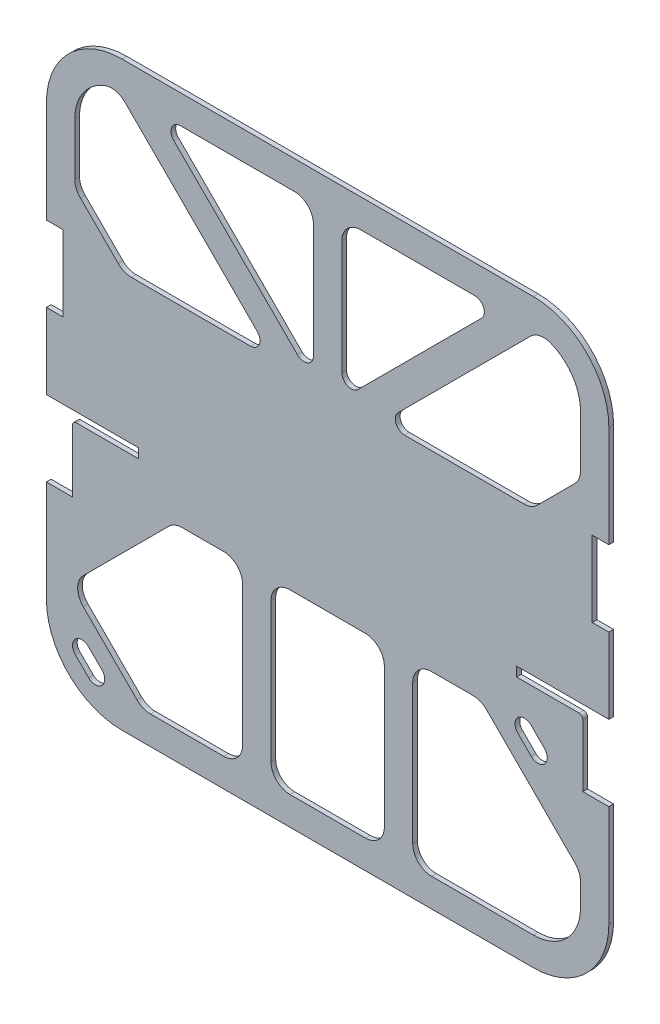
SolidWorks part; units mm, degrees
material "Thornel Mat VMA"
ref_plane "Front Plane" through (0, 0, 0) normal (0, 0, 1) x (1, 0, 0)
ref_plane "Top Plane" through (0, 0, 0) normal (0, 1, 0) x (1, 0, 0)
ref_plane "Right Plane" through (0, 0, 0) normal (1, 0, 0) x (0, 0, -1)
ref_plane "Plane1" through (0, 0, -447.675) normal (0, 0, 1) x (1, 0, 0)
sketch "Sketch1" plane through (0, 0, -447.675) normal (0, 0, 1) x (1, 0, 0)
  line L0 (-25.4, -85.725) -> (25.4, -85.725) construction
  line L1 (25.4, -111.125) -> (-25.4, -111.125) construction
  line L2 (94.488, -85.725) -> (88.9, -85.725)
  line L3 (88.9, -85.725) -> (88.9, -60.325)
  line L4 (88.9, -60.325) -> (-88.9, -60.325) construction
  line L5 (-88.9, -60.325) -> (-88.9, -85.725)
  line L6 (-88.9, -85.725) -> (-94.488, -85.725)
  line L7 (-94.488, -85.725) -> (-94.488, -111.125)
  line L8 (-94.488, -111.125) -> (-63.5, -111.125)
  line L9 (-63.5, -111.125) -> (-63.5, -114.3)
  line L10 (-63.5, -114.3) -> (-84.455, -114.3)
  line L11 (-85.725, -115.57) -> (-85.725, -136.525)
  line L12 (-85.725, -136.525) -> (85.725, -136.525) construction
  line L13 (85.725, -136.525) -> (85.725, -115.57)
  line L14 (84.455, -114.3) -> (63.5, -114.3)
  line L15 (63.5, -114.3) -> (63.5, -111.125)
  line L16 (63.5, -111.125) -> (94.488, -111.125)
  line L17 (94.488, -111.125) -> (94.488, -85.725)
  line L18 (-85.725, -136.525) -> (-94.488, -136.525)
  line L19 (-94.488, -136.525) -> (-94.488, -170.688)
  line L20 (85.725, -136.525) -> (94.488, -136.525)
  line L21 (94.488, -136.525) -> (94.488, -170.688)
  line L22 (69.088, -196.088) -> (-69.088, -196.088)
  line L23 (-88.9, -60.325) -> (-94.488, -60.325)
  line L24 (-94.488, -60.325) -> (-94.488, -26.162)
  line L25 (-69.088, -0.762) -> (69.088, -0.762)
  line L26 (94.488, -26.162) -> (94.488, -60.325)
  line L27 (94.488, -60.325) -> (88.9, -60.325)
  line L28 (0, 0) -> (0, 50000) construction
  line L29 (-84.963, -170.688) -> (-84.963, -163.089) construction
  line L30 (-83.1031, -158.5988) -> (-53.3642, -128.8599) construction
  line L31 (-48.874, -127) -> (-34.925, -127)
  line L32 (-28.575, -133.35) -> (-28.575, -180.213)
  line L33 (-34.925, -186.563) -> (-69.088, -186.563) construction
  line L34 (28.575, -133.35) -> (28.575, -180.213)
  line L35 (-12.7, -127) -> (12.7, -127)
  line L36 (-19.05, -133.35) -> (-19.05, -180.213)
  line L37 (-12.7, -186.563) -> (12.7, -186.563)
  line L38 (19.05, -133.35) -> (19.05, -180.213)
  line L39 (34.925, -186.563) -> (69.088, -186.563)
  line L40 (84.963, -170.688) -> (84.963, -163.089)
  line L41 (83.1031, -158.5988) -> (53.3642, -128.8599)
  line L42 (48.874, -127) -> (34.925, -127)
  line L43 (-84.963, -26.162) -> (-84.963, -43.6712)
  line L44 (-83.1031, -48.1614) -> (-70.4016, -60.8629)
  line L45 (-68.1297, -12.8259) -> (-23.6529, -57.3027)
  line L46 (-25.898, -62.7227) -> (-65.9115, -62.7227)
  line L47 (-49.4612, -10.3589) -> (-11.1125, -10.3589)
  line L48 (-4.7625, -16.7089) -> (-4.7625, -55.0576)
  line L49 (-10.1826, -57.3027) -> (-51.7063, -15.7789)
  line L50 (4.7625, -16.7089) -> (4.7625, -55.0576)
  line L51 (10.1826, -57.3027) -> (51.7063, -15.7789)
  line L52 (49.4612, -10.3589) -> (11.1125, -10.3589)
  line L53 (68.1297, -12.8259) -> (23.6529, -57.3027)
  line L54 (25.898, -62.7227) -> (65.9115, -62.7227)
  line L55 (70.4016, -60.8629) -> (83.1031, -48.1614)
  line L56 (84.963, -43.6712) -> (84.963, -26.162)
  line L57 (-67.5792, -10.3589) -> (-15.2154, -62.7227) construction
  line L58 (66.1388, -128.1641) -> (70.629, -132.6543) construction
  line L59 (68.3839, -125.9191) -> (72.874, -130.4092)
  line L60 (63.8938, -130.4092) -> (68.3839, -134.8993)
  line L61 (-82.5584, -179.6683) -> (-78.0683, -184.1584) construction
  line L62 (-80.3133, -177.4232) -> (-75.8232, -181.9133)
  line L63 (-84.8034, -181.9133) -> (-80.3133, -186.4034)
  line L64 (-82.1401, -166.6161) -> (-64.0531, -184.7031)
  line L65 (-59.563, -186.563) -> (-34.925, -186.563)
  line L66 (-53.3642, -128.8599) -> (-82.1401, -157.6359)
  arc A0 (25.4, -85.725) -> (25.4, -111.125) centre (25.4, -98.425) cw construction
  arc A1 (-25.4, -111.125) -> (-25.4, -85.725) centre (-25.4, -98.425) cw construction
  circle A2 centre (-83.82, -84.8367) radius 1.5875 construction
  arc A3 (94.488, -170.688) -> (69.088, -196.088) centre (69.088, -170.688) cw
  arc A4 (-94.488, -170.688) -> (-69.088, -196.088) centre (-69.088, -170.688) ccw
  arc A5 (69.088, -0.762) -> (94.488, -26.162) centre (69.088, -26.162) cw
  arc A6 (-94.488, -26.162) -> (-69.088, -0.762) centre (-69.088, -26.162) cw
  arc A7 (-84.963, -26.162) -> (-74.9744, -11.4187) centre (-69.088, -26.162) cw
  arc A8 (74.9744, -11.4187) -> (84.963, -26.162) centre (69.088, -26.162) cw
  arc A9 (84.963, -170.688) -> (69.088, -186.563) centre (69.088, -170.688) cw
  arc A10 (-84.963, -170.688) -> (-69.088, -186.563) centre (-69.088, -170.688) ccw construction
  circle A11 centre (-63.5, -114.3) radius 17.4625 construction
  circle A12 centre (-85.725, -136.525) radius 17.4625 construction
  arc A13 (28.575, -133.35) -> (34.925, -127) centre (34.925, -133.35) cw
  arc A14 (53.3642, -128.8599) -> (48.874, -127) centre (48.874, -133.35) ccw
  arc A15 (84.963, -163.089) -> (83.1031, -158.5988) centre (78.613, -163.089) ccw
  arc A16 (28.575, -180.213) -> (34.925, -186.563) centre (34.925, -180.213) ccw
  arc A17 (-19.05, -180.213) -> (-12.7, -186.563) centre (-12.7, -180.213) ccw
  arc A18 (12.7, -186.563) -> (19.05, -180.213) centre (12.7, -180.213) ccw
  arc A19 (12.7, -127) -> (19.05, -133.35) centre (12.7, -133.35) cw
  arc A20 (-12.7, -127) -> (-19.05, -133.35) centre (-12.7, -133.35) ccw
  arc A21 (-28.575, -180.213) -> (-34.925, -186.563) centre (-34.925, -180.213) cw
  arc A22 (-34.925, -127) -> (-28.575, -133.35) centre (-34.925, -133.35) cw
  arc A23 (-53.3642, -128.8599) -> (-48.874, -127) centre (-48.874, -133.35) cw
  arc A24 (-84.963, -163.089) -> (-83.1031, -158.5988) centre (-78.613, -163.089) cw construction
  circle A25 centre (-88.9, -60.325) radius 12.7 construction
  arc A26 (65.9115, -62.7227) -> (70.4016, -60.8629) centre (65.9115, -56.3727) ccw
  arc A27 (83.1031, -48.1614) -> (84.963, -43.6712) centre (78.613, -43.6712) ccw
  arc A28 (69.088, -10.287) -> (84.963, -26.162) centre (69.088, -26.162) cw construction
  arc A29 (68.1297, -12.8259) -> (74.9744, -11.4187) centre (72.6199, -17.316) cw
  arc A30 (4.7625, -16.7089) -> (11.1125, -10.3589) centre (11.1125, -16.7089) cw
  arc A31 (-11.1125, -10.3589) -> (-4.7625, -16.7089) centre (-11.1125, -16.7089) cw
  arc A32 (-84.963, -26.162) -> (-69.088, -10.287) centre (-69.088, -26.162) cw construction
  arc A33 (-68.1297, -12.8259) -> (-74.9744, -11.4187) centre (-72.6199, -17.316) ccw
  arc A34 (-70.4016, -60.8629) -> (-65.9115, -62.7227) centre (-65.9115, -56.3727) ccw
  arc A35 (-84.963, -43.6712) -> (-83.1031, -48.1614) centre (-78.613, -43.6712) ccw
  arc A36 (23.6529, -57.3027) -> (25.898, -62.7227) centre (25.898, -59.5477) ccw
  arc A37 (51.7063, -15.7789) -> (49.4612, -10.3589) centre (49.4612, -13.5339) ccw
  arc A38 (4.7625, -55.0576) -> (10.1826, -57.3027) centre (7.9375, -55.0576) ccw
  arc A39 (-23.6529, -57.3027) -> (-25.898, -62.7227) centre (-25.898, -59.5477) cw
  arc A40 (-4.7625, -55.0576) -> (-10.1826, -57.3027) centre (-7.9375, -55.0576) cw
  arc A41 (-49.4612, -10.3589) -> (-51.7063, -15.7789) centre (-49.4612, -13.5339) ccw
  arc A42 (85.725, -115.57) -> (84.455, -114.3) centre (84.455, -115.57) ccw
  arc A43 (-85.725, -115.57) -> (-84.455, -114.3) centre (-84.455, -115.57) cw
  arc A44 (68.3839, -125.9191) -> (63.8938, -130.4092) centre (66.1388, -128.1641) ccw
  arc A45 (68.3839, -134.8993) -> (72.874, -130.4092) centre (70.629, -132.6543) ccw
  arc A46 (-80.3133, -177.4232) -> (-84.8034, -181.9133) centre (-82.5584, -179.6683) ccw
  arc A47 (-80.3133, -186.4034) -> (-75.8232, -181.9133) centre (-78.0683, -184.1584) ccw
  arc A48 (-64.0531, -184.7031) -> (-59.563, -186.563) centre (-59.563, -180.213) ccw
  arc A49 (-82.1401, -166.6161) -> (-82.1401, -157.6359) centre (-77.65, -162.126) cw
  point P66 (0, -186.563)
  point P80 (-19.05, -186.563)
  point P83 (19.05, -186.563)
  point P90 (-28.575, -186.563)
  point P117 (70.5968, -10.3589)
  point P125 (-70.5968, -10.3589)
  point P132 (18.2329, -62.7227)
  point P137 (4.7625, -62.7227)
  point P142 (-4.7625, -62.7227)
  point P153 (68.3839, -130.4092)
  point P160 (-80.3133, -181.9133)
  point P169 (-62.1933, -186.563)
  dimension "D3" = 25.4
  dimension "D8" = 34.925
  dimension "D10" = 6.35
  dimension "D11" = 25.4
  dimension "D17" = 6.35
  dimension "D18" = 3.175
  dimension "D20" = 1.27
  dimension "D22" = 6.35
  dimension "D1" = 81.788
  dimension "D2" = 195.326
  dimension "D6" = 38.1
  dimension "D7" = 9.525
  dimension "D9" = 12.7
  dimension "D12" = 9.525
  dimension "D13" = 9.525
  dimension "D14" = 4.7625
  dimension "D15" = 9.525
  dimension "D16" = 45
  dimension "D19" = 9.5969
  dimension "D21" = 6.35
  dimension "D23" = 6.35
  dimension "D24" = 6.35
  dimension "D25" = 6.35
  dimension "D26" = 6.35
  dimension "D4" = 9.525
  dimension "D5" = 9.525
extrude "Boss-Extrude1" add sketch "Sketch1" against normal blind 1.5875
